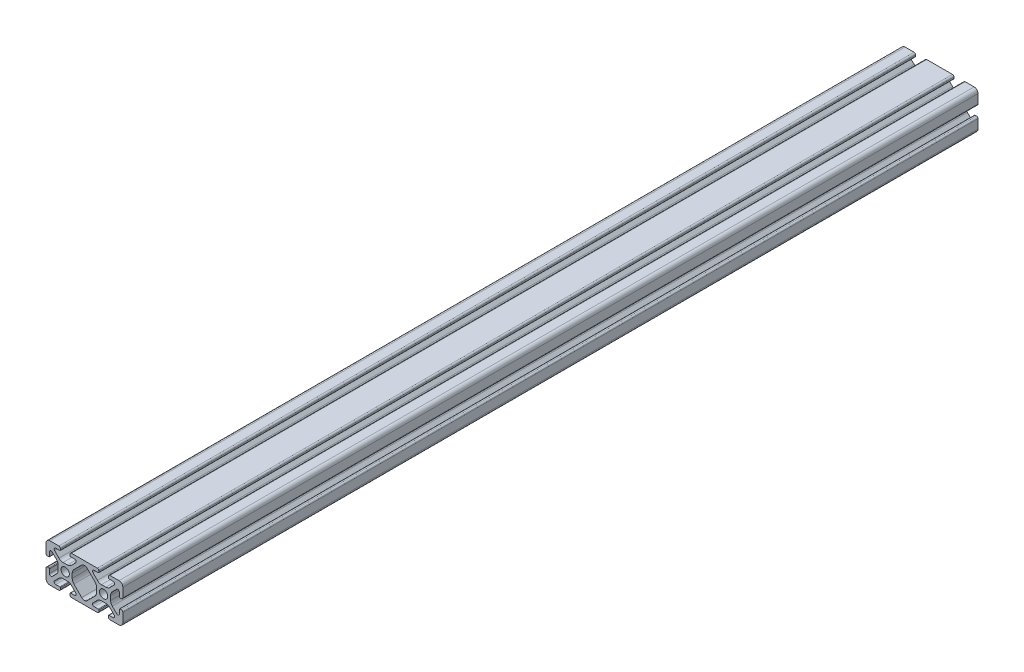
SolidWorks part; units mm, degrees
material "Alliage 1060"
ref_plane "Plan de face" through (0, 0, 0) normal (0, 0, 1) x (1, 0, 0)
ref_plane "Plan de dessus" through (0, 0, 0) normal (0, 1, 0) x (1, 0, 0)
ref_plane "Plan de droite" through (0, 0, 0) normal (1, 0, 0) x (0, 0, -1)
ref_plane "Plan1" through (0, 0, 0) normal (0, 0, -1) x (-1, 0, 0)
sketch "Esquisse1" plane through (0, 0, 0) normal (0, 0, -1) x (-1, 0, 0)
  line L0 (-38, 0) -> (-33.3, 0)
  line L1 (-32.5, 0.8) -> (-32.5, 1.5)
  line L2 (-32.8, 1.8) -> (-34.9184, 1.8)
  line L3 (-35.5064, 3.2196) -> (-33.2547, 5.4713)
  line L4 (-31.1334, 6.35) -> (-28.8666, 6.35)
  line L5 (-26.7453, 5.4713) -> (-24.4936, 3.2196)
  line L6 (-25.0816, 1.8) -> (-27.2, 1.8)
  line L7 (-27.5, 1.5) -> (-27.5, 0.8)
  line L8 (-26.7, 0) -> (-13.3, 0)
  line L9 (-12.5, 0.8) -> (-12.5, 1.5)
  line L10 (-12.8, 1.8) -> (-14.9184, 1.8)
  line L11 (-15.5064, 3.2196) -> (-13.2547, 5.4713)
  line L12 (-11.1334, 6.35) -> (-8.8666, 6.35)
  line L13 (-6.7453, 5.4713) -> (-4.4936, 3.2196)
  line L14 (-5.0816, 1.8) -> (-7.2, 1.8)
  line L15 (-7.5, 1.5) -> (-7.5, 0.8)
  line L16 (-6.7, 0) -> (-2, 0)
  line L17 (0, 2) -> (0, 6.7)
  line L18 (-0.8, 7.5) -> (-1.5, 7.5)
  line L19 (-1.8, 7.2) -> (-1.8, 5.0816)
  line L20 (-3.2196, 4.4936) -> (-5.4713, 6.7453)
  line L21 (-6.35, 8.8666) -> (-6.35, 11.1334)
  line L22 (-5.4713, 13.2547) -> (-3.2196, 15.5064)
  line L23 (-1.8, 14.9184) -> (-1.8, 12.8)
  line L24 (-1.5, 12.5) -> (-0.8, 12.5)
  line L25 (0, 13.3) -> (0, 18)
  line L26 (-2, 20) -> (-6.7, 20)
  line L27 (-7.5, 19.2) -> (-7.5, 18.5)
  line L28 (-7.2, 18.2) -> (-5.0816, 18.2)
  line L29 (-4.4936, 16.7804) -> (-6.7453, 14.5287)
  line L30 (-8.8666, 13.65) -> (-11.1334, 13.65)
  line L31 (-13.2547, 14.5287) -> (-15.5064, 16.7804)
  line L32 (-14.9184, 18.2) -> (-12.8, 18.2)
  line L33 (-12.5, 18.5) -> (-12.5, 19.2)
  line L34 (-13.3, 20) -> (-26.7, 20)
  line L35 (-27.5, 19.2) -> (-27.5, 18.5)
  line L36 (-27.2, 18.2) -> (-25.0816, 18.2)
  line L37 (-24.4936, 16.7804) -> (-26.7453, 14.5287)
  line L38 (-28.8666, 13.65) -> (-31.1334, 13.65)
  line L39 (-33.2547, 14.5287) -> (-35.5064, 16.7804)
  line L40 (-34.9184, 18.2) -> (-32.8, 18.2)
  line L41 (-32.5, 18.5) -> (-32.5, 19.2)
  line L42 (-33.3, 20) -> (-38, 20)
  line L43 (-40, 18) -> (-40, 13.3)
  line L44 (-39.2, 12.5) -> (-38.5, 12.5)
  line L45 (-38.2, 12.8) -> (-38.2, 14.9184)
  line L46 (-36.7804, 15.5064) -> (-34.5287, 13.2547)
  line L47 (-33.65, 11.1334) -> (-33.65, 8.8666)
  line L48 (-34.5287, 6.7453) -> (-36.7804, 4.4936)
  line L49 (-38.2, 5.0816) -> (-38.2, 7.2)
  line L50 (-38.5, 7.5) -> (-39.2, 7.5)
  line L51 (-40, 6.7) -> (-40, 2)
  line L52 (-13.65, 11.1346) -> (-13.65, 8.8654)
  line L53 (-14.5287, 6.7441) -> (-18.5858, 2.687)
  line L54 (-21.4142, 2.687) -> (-25.4713, 6.7441)
  line L55 (-26.35, 8.8654) -> (-26.35, 11.1346)
  line L56 (-25.4713, 13.2559) -> (-21.4142, 17.313)
  line L57 (-18.5858, 17.313) -> (-14.5287, 13.2559)
  arc A0 (-40, 2) -> (-38, 0) centre (-38, 2) ccw
  arc A1 (-33.3, 0) -> (-32.5, 0.8) centre (-33.3, 0.8) ccw
  arc A2 (-32.5, 1.5) -> (-32.8, 1.8) centre (-32.8, 1.5) ccw
  arc A3 (-34.9184, 1.8) -> (-35.5064, 3.2196) centre (-34.9184, 2.6316) cw
  arc A4 (-33.2547, 5.4713) -> (-31.1334, 6.35) centre (-31.1334, 3.35) cw
  arc A5 (-28.8666, 6.35) -> (-26.7453, 5.4713) centre (-28.8666, 3.35) cw
  arc A6 (-24.4936, 3.2196) -> (-25.0816, 1.8) centre (-25.0816, 2.6316) cw
  arc A7 (-27.2, 1.8) -> (-27.5, 1.5) centre (-27.2, 1.5) ccw
  arc A8 (-27.5, 0.8) -> (-26.7, 0) centre (-26.7, 0.8) ccw
  arc A9 (-13.3, 0) -> (-12.5, 0.8) centre (-13.3, 0.8) ccw
  arc A10 (-12.5, 1.5) -> (-12.8, 1.8) centre (-12.8, 1.5) ccw
  arc A11 (-14.9184, 1.8) -> (-15.5064, 3.2196) centre (-14.9184, 2.6316) cw
  arc A12 (-13.2547, 5.4713) -> (-11.1334, 6.35) centre (-11.1334, 3.35) cw
  arc A13 (-8.8666, 6.35) -> (-6.7453, 5.4713) centre (-8.8666, 3.35) cw
  arc A14 (-4.4936, 3.2196) -> (-5.0816, 1.8) centre (-5.0816, 2.6316) cw
  arc A15 (-7.2, 1.8) -> (-7.5, 1.5) centre (-7.2, 1.5) ccw
  arc A16 (-7.5, 0.8) -> (-6.7, 0) centre (-6.7, 0.8) ccw
  arc A17 (-2, 0) -> (0, 2) centre (-2, 2) ccw
  arc A18 (0, 6.7) -> (-0.8, 7.5) centre (-0.8, 6.7) ccw
  arc A19 (-1.5, 7.5) -> (-1.8, 7.2) centre (-1.5, 7.2) ccw
  arc A20 (-1.8, 5.0816) -> (-3.2196, 4.4936) centre (-2.6316, 5.0816) cw
  arc A21 (-5.4713, 6.7453) -> (-6.35, 8.8666) centre (-3.35, 8.8666) cw
  arc A22 (-6.35, 11.1334) -> (-5.4713, 13.2547) centre (-3.35, 11.1334) cw
  arc A23 (-3.2196, 15.5064) -> (-1.8, 14.9184) centre (-2.6316, 14.9184) cw
  arc A24 (-1.8, 12.8) -> (-1.5, 12.5) centre (-1.5, 12.8) ccw
  arc A25 (-0.8, 12.5) -> (0, 13.3) centre (-0.8, 13.3) ccw
  arc A26 (0, 18) -> (-2, 20) centre (-2, 18) ccw
  arc A27 (-6.7, 20) -> (-7.5, 19.2) centre (-6.7, 19.2) ccw
  arc A28 (-7.5, 18.5) -> (-7.2, 18.2) centre (-7.2, 18.5) ccw
  arc A29 (-5.0816, 18.2) -> (-4.4936, 16.7804) centre (-5.0816, 17.3684) cw
  arc A30 (-6.7453, 14.5287) -> (-8.8666, 13.65) centre (-8.8666, 16.65) cw
  arc A31 (-11.1334, 13.65) -> (-13.2547, 14.5287) centre (-11.1334, 16.65) cw
  arc A32 (-15.5064, 16.7804) -> (-14.9184, 18.2) centre (-14.9184, 17.3684) cw
  arc A33 (-12.8, 18.2) -> (-12.5, 18.5) centre (-12.8, 18.5) ccw
  arc A34 (-12.5, 19.2) -> (-13.3, 20) centre (-13.3, 19.2) ccw
  arc A35 (-26.7, 20) -> (-27.5, 19.2) centre (-26.7, 19.2) ccw
  arc A36 (-27.5, 18.5) -> (-27.2, 18.2) centre (-27.2, 18.5) ccw
  arc A37 (-25.0816, 18.2) -> (-24.4936, 16.7804) centre (-25.0816, 17.3684) cw
  arc A38 (-26.7453, 14.5287) -> (-28.8666, 13.65) centre (-28.8666, 16.65) cw
  arc A39 (-31.1334, 13.65) -> (-33.2547, 14.5287) centre (-31.1334, 16.65) cw
  arc A40 (-35.5064, 16.7804) -> (-34.9184, 18.2) centre (-34.9184, 17.3684) cw
  arc A41 (-32.8, 18.2) -> (-32.5, 18.5) centre (-32.8, 18.5) ccw
  arc A42 (-32.5, 19.2) -> (-33.3, 20) centre (-33.3, 19.2) ccw
  arc A43 (-38, 20) -> (-40, 18) centre (-38, 18) ccw
  arc A44 (-40, 13.3) -> (-39.2, 12.5) centre (-39.2, 13.3) ccw
  arc A45 (-38.5, 12.5) -> (-38.2, 12.8) centre (-38.5, 12.8) ccw
  arc A46 (-38.2, 14.9184) -> (-36.7804, 15.5064) centre (-37.3684, 14.9184) cw
  arc A47 (-34.5287, 13.2547) -> (-33.65, 11.1334) centre (-36.65, 11.1334) cw
  arc A48 (-33.65, 8.8666) -> (-34.5287, 6.7453) centre (-36.65, 8.8666) cw
  arc A49 (-36.7804, 4.4936) -> (-38.2, 5.0816) centre (-37.3684, 5.0816) cw
  arc A50 (-38.2, 7.2) -> (-38.5, 7.5) centre (-38.5, 7.2) ccw
  arc A51 (-39.2, 7.5) -> (-40, 6.7) centre (-39.2, 6.7) ccw
  circle A52 centre (-10, 10) radius 2.15
  circle A53 centre (-30, 10) radius 2.15
  arc A54 (-13.65, 8.8654) -> (-14.5287, 6.7441) centre (-16.65, 8.8654) cw
  arc A55 (-18.5858, 2.687) -> (-21.4142, 2.687) centre (-20, 4.1012) cw
  arc A56 (-25.4713, 6.7441) -> (-26.35, 8.8654) centre (-23.35, 8.8654) cw
  arc A57 (-26.35, 11.1346) -> (-25.4713, 13.2559) centre (-23.35, 11.1346) cw
  arc A58 (-21.4142, 17.313) -> (-18.5858, 17.313) centre (-20, 15.8988) cw
  arc A59 (-14.5287, 13.2559) -> (-13.65, 11.1346) centre (-16.65, 11.1346) cw
extrude "Extrusion1" add sketch "Esquisse1" against normal blind 445.3
